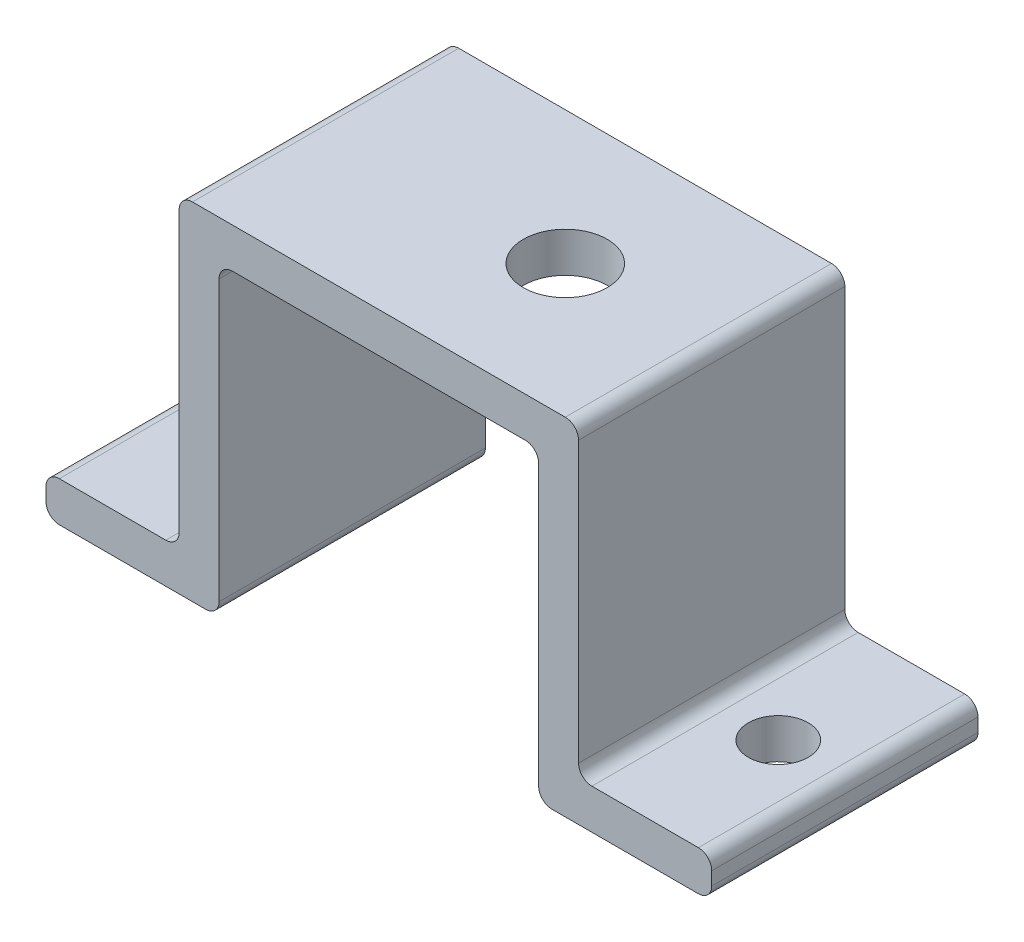
SolidWorks part; units mm, degrees
ref_plane "Front Plane" through (0, 0, 0) normal (0, 0, 1) x (1, 0, 0)
ref_plane "Top Plane" through (0, 0, 0) normal (0, 1, 0) x (1, 0, 0)
ref_plane "Right Plane" through (0, 0, 0) normal (1, 0, 0) x (0, 0, -1)
sketch "Sketch2" plane through (0, 0, 0) normal (0, 0, 1) x (1, 0, 0)
  line L1 (-12, 0) -> (12, 0)
  line L2 (-15, -20) -> (-15, 3)
  line L3 (-15, 3) -> (15, 3)
  line L4 (15, -20) -> (15, 3)
  line L15 (-15, -20) -> (-25, -20)
  line L16 (-12, 0) -> (-12, -23)
  line L17 (-12, -23) -> (-25, -23)
  line L18 (-25, -20) -> (-25, -23)
  line L19 (15, -20) -> (25, -20)
  line L20 (12, 0) -> (12, -23)
  line L21 (12, -23) -> (25, -23)
  line L22 (25, -20) -> (25, -23)
  point P0 (0, 0)
  point P23 (-12, -11.5)
  point P26 (0, 0)
  dimension "D1" = 50
  dimension "D2" = 24
  dimension "D3" = 3
  dimension "D4" = 3
  dimension "D5" = 3
  dimension "D6" = 23
extrude "Boss-Extrude1" add sketch "Sketch2" along normal blind 20
sketch "Sketch3" plane through (0, 3, 0) normal (0, 1, 0) x (1, 0, 0)
  line L0 (-15, -10) -> (15, -10) construction
  line L1 (-15, -20) -> (-15, 0) construction
  line L2 (15, -20) -> (15, 0) construction
  line L3 (15, -20) -> (15, 0) construction
  circle A0 centre (4, -10) radius 3.15
  dimension "D1" = 6.3
  dimension "D2" = 11
extrude "Cut-Extrude1" cut sketch "Sketch3" against normal through all
sketch "Sketch5" plane through (0, -20, 0) normal (0, 1, 0) x (1, 0, 0)
  line L0 (-20, -10) -> (20, -10) construction
  line L3 (0, 0) -> (0, -20) construction
  line L6 (15, 0) -> (-15, 0) construction
  line L7 (15, -20) -> (-15, -20) construction
  circle A0 centre (-20, -10) radius 2.25
  circle A1 centre (20, -10) radius 2.25
  point P2 (0, -10)
  dimension "D1" = 4.5
  dimension "D2" = 40
extrude "Cut-Extrude2" cut sketch "Sketch5" against normal through all
fillet "Fillet1" radius 1 12 edges at (25, -20, 10) (-25, -23, 10) (25, -23, 10) (-25, -20, 10) (-15, -20, 10) (-15, 3, 10) (15, 3, 10) (15, -20, 10) (12, -23, 10) (-12, -23, 10) (-12, 0, 10) (12, 0, 10)
